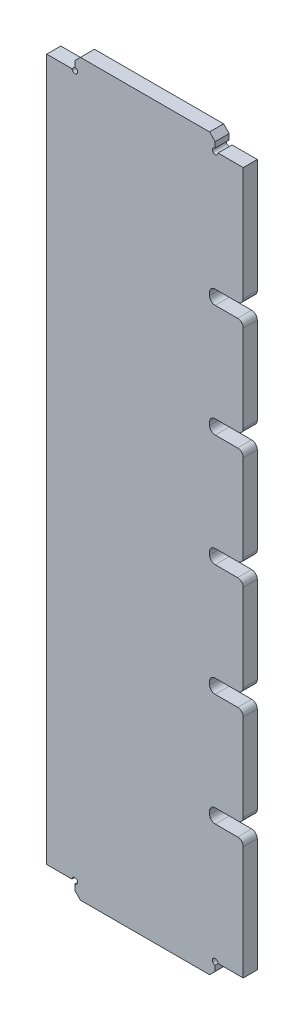
SolidWorks part; units mm, degrees
ref_plane "前基準面" through (0, 0, 0) normal (0, 0, 1) x (1, 0, 0)
ref_plane "上基準面" through (0, 0, 0) normal (0, 1, 0) x (1, 0, 0)
ref_plane "右基準面" through (0, 0, 0) normal (1, 0, 0) x (0, 0, -1)
sketch "草圖1" plane through (0, 0, 0) normal (0, 0, 1) x (1, 0, 0)
  line L0 (-25, 2) -> (-23, 0)
  line L3 (-23, 0) -> (23, 0)
  line L5 (23, 0) -> (25, 2)
  line L6 (-25, 2) -> (-25, 4)
  line L10 (-35, 5) -> (-35, 255)
  line L14 (35, 5) -> (35, 47.5)
  line L15 (-26, 5) -> (-35, 5)
  line L16 (25, 2) -> (25, 4)
  line L17 (26, 5) -> (35, 5)
  line L18 (-35, 130) -> (35, 130) construction
  line L19 (26, 255) -> (35, 255)
  line L20 (25, 258) -> (25, 256)
  line L21 (-26, 255) -> (-35, 255)
  line L22 (-25, 258) -> (-25, 256)
  line L23 (23, 260) -> (25, 258)
  line L24 (-23, 260) -> (23, 260)
  line L25 (-25, 258) -> (-23, 260)
  line L26 (23, 172.5) -> (35, 172.5)
  line L27 (23, 212.5) -> (35, 212.5)
  line L28 (23, 212.5) -> (23, 207.5)
  line L29 (23, 207.5) -> (35, 207.5)
  line L31 (23, 172.5) -> (23, 167.5)
  line L32 (23, 167.5) -> (35, 167.5)
  line L34 (23, 132.5) -> (35, 132.5)
  line L35 (23, 132.5) -> (23, 127.5)
  line L36 (23, 127.5) -> (35, 127.5)
  line L38 (23, 92.5) -> (35, 92.5)
  line L39 (23, 92.5) -> (23, 87.5)
  line L40 (23, 87.5) -> (35, 87.5)
  line L42 (23, 52.5) -> (35, 52.5)
  line L43 (23, 52.5) -> (23, 47.5)
  line L44 (23, 47.5) -> (35, 47.5)
  line L46 (35, 212.5) -> (35, 255)
  line L47 (35, 172.5) -> (35, 207.5)
  line L48 (35, 132.5) -> (35, 167.5)
  line L49 (35, 92.5) -> (35, 127.5)
  line L50 (35, 52.5) -> (35, 87.5)
  arc A0 (-25, 4) -> (-26, 5) centre (-25, 5) ccw
  arc A1 (26, 5) -> (25, 4) centre (25, 5) ccw
  arc A2 (26, 255) -> (25, 256) centre (25, 255) cw
  arc A3 (-25, 256) -> (-26, 255) centre (-25, 255) cw
  point P1 (25, 0)
  point P2 (-25, 0)
  point P8 (0, 0)
  point P30 (-25, 260)
  point P31 (25, 260)
  point P49 (23, 130)
  dimension "D8" = 1
  dimension "D6" = 12
  dimension "D1" = 50
  dimension "D2" = 70
  dimension "D3" = 250
  dimension "D7" = 3
  dimension "D9" = 5
  dimension "D10" = 40
  dimension "D11" = 5
extrude "填料-伸長1" add sketch "草圖1" along normal mid plane 5 contours L10 L21 A3 L22 L25 L24 L23 L20 A2 L19 L46 L27 L28 L29 L47 L26 L31 L32 L48 L34 L35 L36 L49 L38 L39 L40 L50 L42 L43 L44 L14 L17 A1 L16 L5 L3 L0 L6 A0 L15
fillet "圓角1" radius 2 20 edges at (23, 52.5, 0) (23, 47.5, 0) (35, 47.5, 0) (35, 52.5, 0) (23, 92.5, 0) (23, 87.5, 0) (35, 87.5, 0) (35, 92.5, 0) (23, 127.5, 0) (23, 132.5, 0) (35, 127.5, 0) (35, 132.5, 0) (23, 212.5, 0) (23, 207.5, 0) (35, 212.5, 0) (35, 207.5, 0) (35, 167.5, 0) (35, 172.5, 0) (23, 167.5, 0) (23, 172.5, 0)
